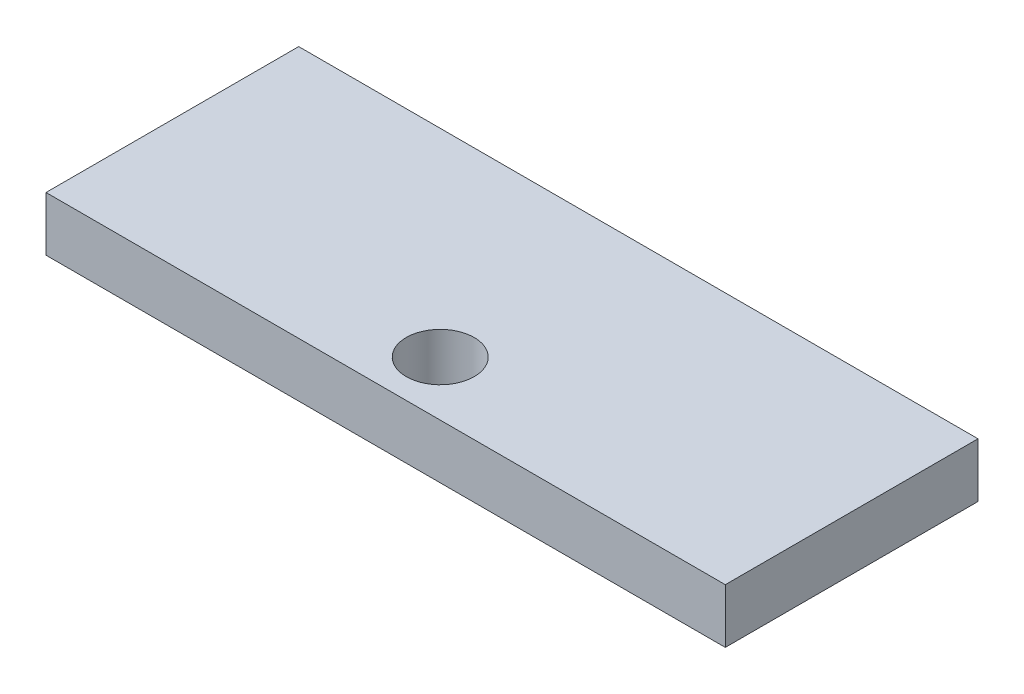
SolidWorks part; units mm, degrees
ref_plane "Front Plane" through (0, 0, 0) normal (0, 0, 1) x (1, 0, 0)
ref_plane "Top Plane" through (0, 0, 0) normal (0, 1, 0) x (1, 0, 0)
ref_plane "Right Plane" through (0, 0, 0) normal (1, 0, 0) x (0, 0, -1)
sketch "Sketch1" plane through (0, 0, 0) normal (0, 1, 0) x (1, 0, 0)
  line L1 (12.5, -4.75) -> (-12.5, -4.75)
  line L2 (12.5, -4.75) -> (12.5, 4.75)
  line L3 (12.5, 4.75) -> (-12.5, 4.75)
  line L4 (-12.5, -4.75) -> (-12.5, 4.75)
  line L5 (12.5, -4.75) -> (-12.5, 4.75) construction
  line L6 (12.5, 4.75) -> (-12.5, -4.75) construction
  circle A0 centre (0, -2.7415) radius 1.25 construction
  circle A1 centre (0, -2.7415) radius 1.25
  point P0 (0, 0)
  dimension "D1" = 25
  dimension "D2" = 9.5
extrude "Boss-Extrude1" add sketch "Sketch1" along normal blind 2
chamfer "Chamfer1" distance 0.2 angle 45 4 edges at (0, 0, -4.75) (0, 2, -4.75) (-12.5, 1, -4.75) (12.5, 1, -4.75)
